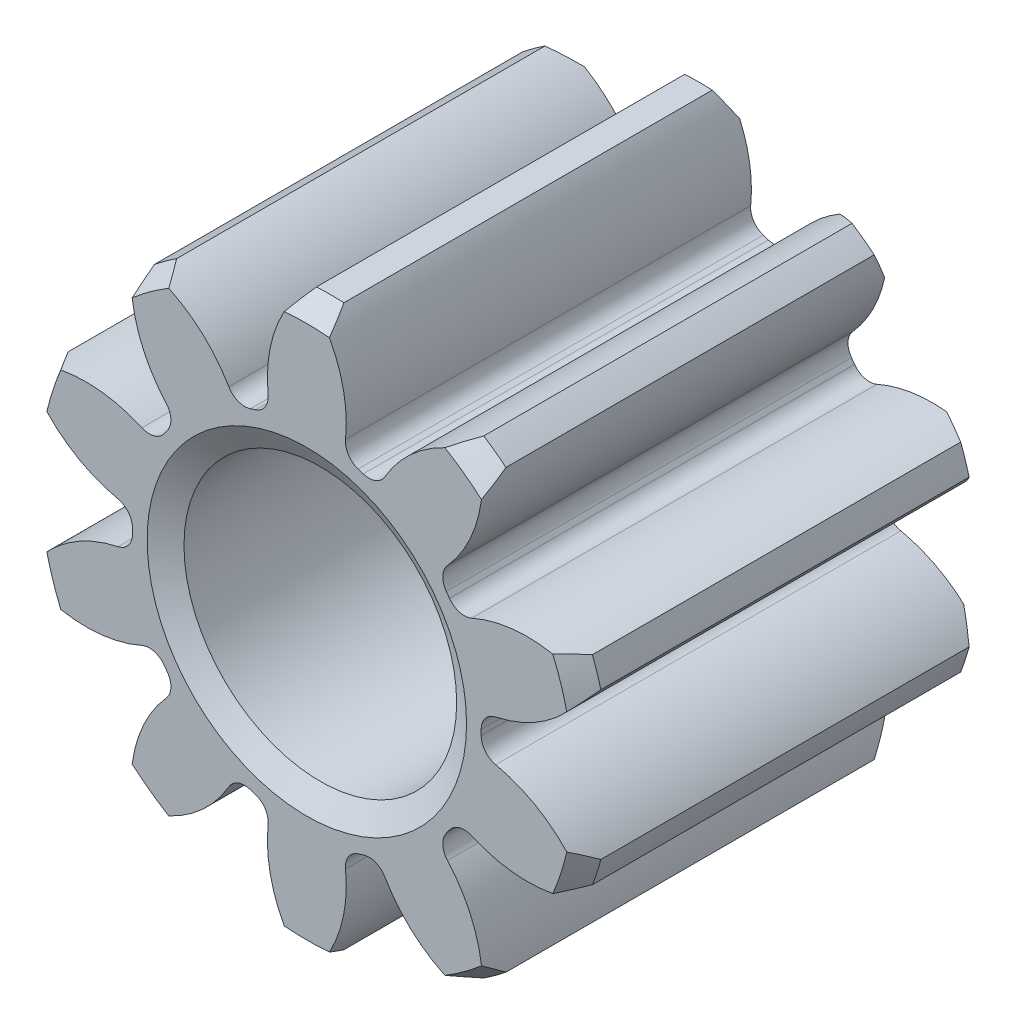
SolidWorks part; units mm, degrees
ref_plane "Front Plane" through (0, 0, 0) normal (0, 0, 1) x (1, 0, 0)
ref_plane "Top Plane" through (0, 0, 0) normal (0, 1, 0) x (1, 0, 0)
ref_plane "Right Plane" through (0, 0, 0) normal (1, 0, 0) x (0, 0, -1)
sketch "Sketch1" plane through (0, 0, 0) normal (0, 0, 1) x (1, 0, 0)
  line L0 (0, 0) -> (0, 1.5) construction
  line L1 (-0.4821, 1.6755) -> (0.4821, 1.3245) construction
  circle A0 centre (0, 0) radius 1.125 construction
  circle A1 centre (0, 0) radius 1.8 construction
  circle A2 centre (0, 0) radius 1.5 construction
  circle A3 centre (0, 0) radius 1.4095 construction
  circle A5 centre (0, 0) radius 0.625 construction
  point P8 (0.15, 0)
  point P13 (5, 0)
  dimension "OD" = 3.6
  dimension "Root Diameter" = 2.25
  dimension "Gear Pitch Diameter" = 3
  dimension "Base Diameter" = 2.8191
  dimension "For Shaft Diameter" = 1.25
  dimension "Pressure Angle" = 20
  dimension "Number of Teeth" = 10
  dimension "Module" = 0.3
sketch "Sketch2" plane through (0, 0, 0) normal (1, 0, 0) x (0, 0, -1)
  line L0 (-1.3, 0) -> (1.3, 0) construction
  line L1 (1.3, 1.8) -> (1.3, -1.8) construction
  line L3 (-1.3, 1.8) -> (1.3, 1.8) construction
  line L5 (-1.3, 12.5) -> (-1.3, -12.5) construction
  point P2 (0, 1.8)
  dimension "Overall Width" = 2.6
  dimension "Face Width" = 1.3
sketch "Sketch3" plane through (0, 0, 0) normal (0, 0, 1) x (1, 0, 0)
  circle A0 centre (0, 0) radius 1.8
  circle A1 centre (0, 0) radius 1.8 construction
extrude "Boss-Extrude1" add sketch "Sketch3" against normal up to vertex (1.3 mm away) and the other way up to vertex (1.3 mm away) up to point (0, 0, -1.3) other way up to point (0, 0, 1.3)
sketch "Sketch5" plane through (0, 0, 0) normal (1, 0, 0) x (0, 0, -1)
  line L1 (-5.9977, 0) -> (8.6948, 0) construction
  line L2 (1.3, 0) -> (-1.3, 0) construction
  line L19 (1.3, -1.8) -> (1.3, 1.8) construction
  line L20 (-1.3, 0) -> (1.3, 0)
  line L21 (-1.3, 0) -> (-1.3, 0.875)
  line L22 (-1.3, 0.875) -> (1.3, 0.875)
  line L23 (1.3, 0) -> (1.3, 0.875)
  line L24 (-1.3, 1.8) -> (-1.3, -1.8) construction
  dimension "D1" = 1.75
revolve "Cut-Revolve1" cut sketch "Sketch5" angle 360 about L1
chamfer "Chamfer1" distance 0.15 angle 30 4 edges at (1.8, 0, -1.3) (0.875, 0, -1.3) (1.8, 0, 1.3) (0.875, 0, 1.3)
sketch "Sketch4" plane through (0, 0, 0) normal (0, 0, 1) x (1, 0, 0)
  line L0 (1.1188, -0.1178) -> (1.1188, 0.1178)
  arc A3 (1.7371, 0.4718) -> (1.7371, -0.4718) centre (0, 0) cw
  circle A4 centre (0, 0) radius 1.8 construction
  arc A5 (1.7371, 0.4718) -> (1.1188, 0.1178) centre (1.0278, 0.9937) cw
  circle A6 centre (0, 0) radius 1.125 construction
  arc A7 (1.7371, -0.4718) -> (1.1188, -0.1178) centre (1.0278, -0.9937) ccw
  spline S0 degree 4 poles (1.3953, 0.1997) (1.396, 0.1998) (1.3978, 0.2002) (1.4012, 0.2009) (1.4067, 0.2023) (1.4137, 0.2044) (1.4226, 0.2074) (1.433, 0.2113) (1.4443, 0.216) (1.4565, 0.2216) (1.4685, 0.2276) (1.4803, 0.2339) (1.4919, 0.2405) (1.5058, 0.2488) (1.5223, 0.2594) (1.5412, 0.2725) (1.5622, 0.2882) (1.583, 0.3051) (1.6032, 0.3225) (1.623, 0.3409) (1.6418, 0.3593) (1.6608, 0.3793) (1.678, 0.3981) (1.6967, 0.4201) (1.7115, 0.4381) (1.7305, 0.4627) (1.7414, 0.4775) (1.754, 0.4952) (1.7594, 0.5032) (1.7628, 0.5081) knots 0 0 0 0 0 0.005377 0.015084 0.028532 0.04661 0.064855 0.092111 0.119476 0.146842 0.174209 0.201575 0.228941 0.256307 0.307035 0.361767 0.4165 0.471232 0.525964 0.580697 0.635429 0.690161 0.744894 0.799626 0.854358 0.909091 0.954545 1 1 1 1 1 construction
  spline S1 degree 4 poles (1.3953, 0.1997) (1.396, 0.1998) (1.3978, 0.2002) (1.4012, 0.2009) (1.4067, 0.2023) (1.4137, 0.2044) (1.4226, 0.2074) (1.433, 0.2113) (1.4443, 0.216) (1.4565, 0.2216) (1.4685, 0.2276) (1.4803, 0.2339) (1.4919, 0.2405) (1.5058, 0.2488) (1.5223, 0.2594) (1.5412, 0.2725) (1.5622, 0.2882) (1.583, 0.3051) (1.6032, 0.3225) (1.623, 0.3409) (1.6418, 0.3593) (1.6608, 0.3793) (1.678, 0.3981) (1.6967, 0.4201) (1.7115, 0.4381) (1.7264, 0.4574) (1.7335, 0.4669) (1.7371, 0.4718) knots 0 0 0 0 0 0.005377 0.015084 0.028532 0.04661 0.064855 0.092111 0.119476 0.146842 0.174209 0.201575 0.228941 0.256307 0.307035 0.361767 0.4165 0.471232 0.525964 0.580697 0.635429 0.690161 0.744894 0.799626 0.854358 0.909091 0.909091 0.909091 0.909091 0.909091 construction
  spline S2 degree 4 poles (1.3953, -0.1997) (1.396, -0.1998) (1.3978, -0.2002) (1.4012, -0.2009) (1.4067, -0.2023) (1.4137, -0.2044) (1.4226, -0.2074) (1.433, -0.2113) (1.4443, -0.216) (1.4565, -0.2216) (1.4685, -0.2276) (1.4803, -0.2339) (1.4919, -0.2405) (1.5058, -0.2488) (1.5223, -0.2594) (1.5412, -0.2725) (1.5622, -0.2882) (1.583, -0.3051) (1.6032, -0.3225) (1.623, -0.3409) (1.6418, -0.3593) (1.6608, -0.3793) (1.678, -0.3981) (1.6967, -0.4201) (1.7115, -0.4381) (1.7305, -0.4627) (1.7414, -0.4775) (1.754, -0.4952) (1.7594, -0.5032) (1.7628, -0.5081) knots 0 0 0 0 0 0.005377 0.015084 0.028532 0.04661 0.064855 0.092111 0.119476 0.146842 0.174209 0.201575 0.228941 0.256307 0.307035 0.361767 0.4165 0.471232 0.525964 0.580697 0.635429 0.690161 0.744894 0.799626 0.854358 0.909091 0.954545 1 1 1 1 1 construction
  spline S3 degree 4 poles (1.3953, -0.1997) (1.396, -0.1998) (1.3978, -0.2002) (1.4012, -0.2009) (1.4067, -0.2023) (1.4137, -0.2044) (1.4226, -0.2074) (1.433, -0.2113) (1.4443, -0.216) (1.4565, -0.2216) (1.4685, -0.2276) (1.4803, -0.2339) (1.4919, -0.2405) (1.5058, -0.2488) (1.5223, -0.2594) (1.5412, -0.2725) (1.5622, -0.2882) (1.583, -0.3051) (1.6032, -0.3225) (1.623, -0.3409) (1.6418, -0.3593) (1.6608, -0.3793) (1.678, -0.3981) (1.6967, -0.4201) (1.7115, -0.4381) (1.7264, -0.4574) (1.7335, -0.4669) (1.7371, -0.4718) knots 0 0 0 0 0 0.005377 0.015084 0.028532 0.04661 0.064855 0.092111 0.119476 0.146842 0.174209 0.201575 0.228941 0.256307 0.307035 0.361767 0.4165 0.471232 0.525964 0.580697 0.635429 0.690161 0.744894 0.799626 0.854358 0.909091 0.909091 0.909091 0.909091 0.909091 construction
  dimension "D1" = 0.2356
extrude "Cut-Extrude1" cut sketch "Sketch4" against normal through all both and the other way through all
fillet "Fillet1" radius 0.1178 2 edges at (1.1188, -0.1178, 0) (1.1188, 0.1178, 0)
pattern_circular "CirPattern1" count 10 over 360 about axis through (0, 0, 0) along (0, 0, 1) of "Cut-Extrude1", "Fillet1"
equation "\"Number of Teeth\"= 10"
equation "\"Module\"= 0.3"
equation "\"Diametral Pitch\"= 1 / \"Module\""
equation "\"Dedendum\"= 1.25 / \"Diametral Pitch\""
equation "\"Pitch Diameter\"= \"Module\" * \"Number of Teeth\""
equation "\"Root Diameter\"= \"Pitch Diameter\" - ( 2 * \"Dedendum\" )"
equation "\"Root Diameter@Sketch1\"=\"Root Diameter\""
equation "\"OD@Sketch1\" = \"Outside Diameter\""
equation "\"D1@CirPattern1\"=\"Number of Teeth\""
equation "\"Pressure Angle\"= 20"
equation "\"Base Diameter\"= \"Pitch Diameter\" * cos ( \"Pressure Angle\" )"
equation "\"Outside Diameter\"= ( \"Number of Teeth\" + 2 ) / \"Diametral Pitch\""
equation "\"Pitch Angle\"= 360deg / \"Number of Teeth\""
equation "\"Alpha\"= sqr ( \"Pitch Diameter\" ^ 2 - \"Base Diameter\" ^ 2 ) / \"Base Diameter\" * 180 / PI - \"Pressure Angle\""
equation "\"Beta\"= ( \"Pitch Angle\" / 4 - \"Alpha\" )"
equation "\"Phi\"= sqr ( ( \"Outside Diameter\" / 2 ) ^ 2 - ( \"Base Diameter\" / 2 ) ^ 2 ) / ( \"Base Diameter\" / 2 )"
equation "\"Addendum\"= 1 / \"Diametral Pitch\""
equation "\"WorkingDepth\"= 2 / \"Diametral Pitch\""
equation "\"WholeDepth\"= 2.25 / \"Diametral Pitch\""
equation "\"Clearance\"= 0.25 / \"Diametral Pitch\""
equation "\"ToothThickness\"= ( pi * 2 ) / \"Diametral Pitch\""
equation "\"CircularPitch\"= pi / \"Diametral Pitch\""
equation "\"Number of Teeth@Sketch1\"=\"Number of Teeth\""
equation "\"Module@Sketch1\"=\"Module\""
equation "\"Pressure Angle@Sketch1\"=\"Pressure Angle\""
equation "\"Gear Pitch Diameter@Sketch1\"=\"Pitch Diameter\""
equation "\"Base Diameter@Sketch1\"=\"Base Diameter\""
equation "\"Fillet\"= \"Clearance\" * cos ( \"Pressure Angle\" ) * tan ( ( 90 + \"Pressure Angle\" ) / 2 )"
equation "\"D1\"= \"Fillet\""
equation "\"D1\"= \"Set Screw Pitch@Sketch1\" * .75"
equation "\"D1\"= \"Set Screw Diameter@Sketch1\" / 2"
equation "\"D3\"= \"Set Screw Pitch@Sketch1\" +  ( \"Hub Diameter@Sketch1\" / 2 ) "
equation "\"D4\"= \"Set Screw Pitch@Sketch1\""
equation "\"D2\"= \"Fillet\" * 2"
equation "\"D1\"= \"Fillet\" * 2"
equation "\"D1@Chamfer2\"=\"Fillet\""
equation "\"D1@Sketch4\"=\"CircularPitch\"*0.25"
equation "\"D1@Fillet1\"=\"CircularPitch\"*0.125"
